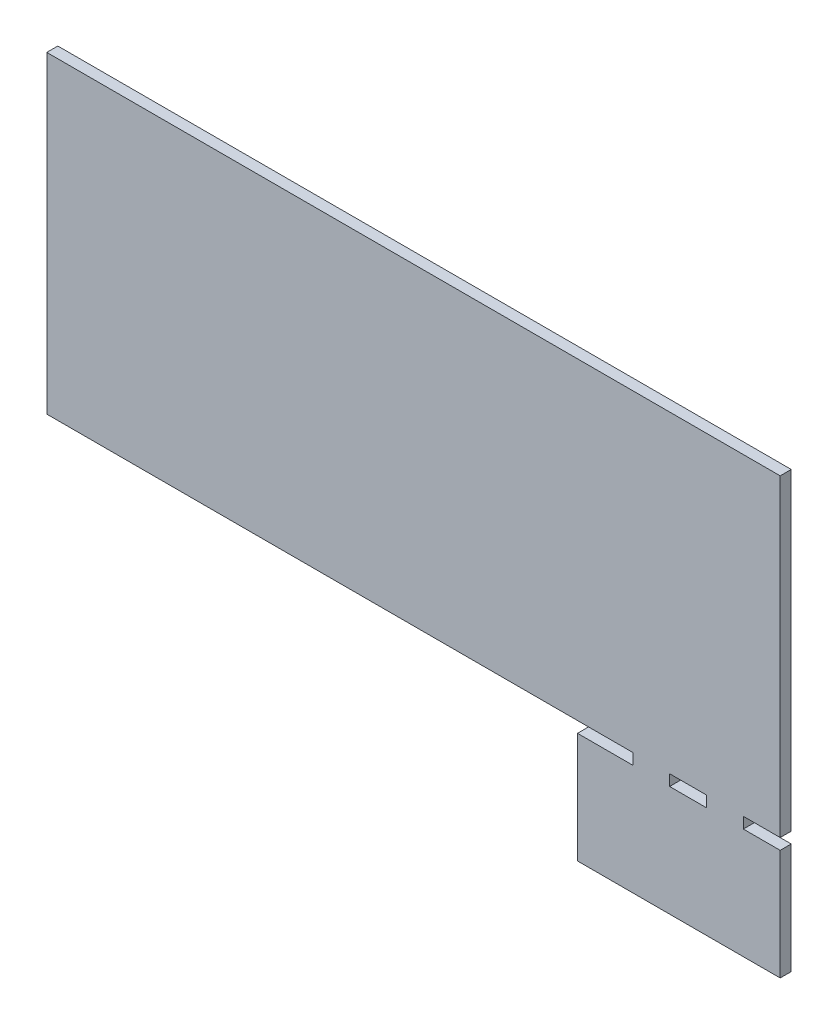
SolidWorks part; units mm, degrees
ref_plane "Front Plane" through (0, 0, 0) normal (0, 0, 1) x (1, 0, 0)
ref_plane "Top Plane" through (0, 0, 0) normal (0, 1, 0) x (1, 0, 0)
ref_plane "Right Plane" through (0, 0, 0) normal (1, 0, 0) x (0, 0, -1)
sketch "Sketch1" plane through (0, 0, 0) normal (0, 0, 1) x (1, 0, 0)
  line L1 (-27.5, -27.5) -> (27.5, -27.5)
  line L2 (-27.5, -27.5) -> (-27.5, 27.5)
  line L3 (-27.5, 27.5) -> (27.5, 27.5)
  line L4 (27.5, -27.5) -> (27.5, 27.5)
  line L5 (0, 27.5) -> (0, -27.5) construction
  line L6 (-27.5, 0) -> (27.5, 0) construction
  point P0 (0, 0)
  dimension "D1" = 55
  dimension "D2" = 55
extrude "Boss-Extrude1" add sketch "Sketch1" along normal blind 3
sketch "Sketch2" plane through (0, 0, 3) normal (0, 0, 1) x (1, 0, 0)
  line L0 (-27.5, -24.5) -> (27.5, -24.5) construction
  line L1 (-27.5, 27.5) -> (-27.5, -27.5) construction
  line L2 (27.5, -27.5) -> (27.5, 27.5) construction
  line L3 (-27.5, -27.5) -> (27.5, -27.5) construction
  line L4 (17.5, -24.5) -> (17.5, -27.5) construction
  line L5 (27.5, -27.5) -> (27.5, 27.5) construction
  line L6 (7.5, -24.5) -> (7.5, -27.5) construction
  line L7 (27.5, -24.5) -> (17.5, -24.5)
  line L8 (27.5, -24.5) -> (27.5, -27.5)
  line L9 (27.5, -27.5) -> (17.5, -27.5)
  line L10 (17.5, -24.5) -> (17.5, -27.5)
  line L11 (-12.5, -24.5) -> (-12.5, -27.5) construction
  line L12 (7.5, -24.5) -> (-2.5, -24.5)
  line L13 (7.5, -24.5) -> (7.5, -27.5)
  line L14 (7.5, -27.5) -> (-2.5, -27.5)
  line L15 (-2.5, -24.5) -> (-2.5, -27.5)
  line L17 (-12.5, -24.5) -> (-27.5, -24.5)
  line L18 (-12.5, -24.5) -> (-12.5, -27.5)
  line L19 (-12.5, -27.5) -> (-27.5, -27.5)
  line L20 (-27.5, -24.5) -> (-27.5, -27.5)
  dimension "D1" = 3
  dimension "D2" = 10
  dimension "D3" = 10
  dimension "D4" = 10
  dimension "D5" = 10
extrude "Cut-Extrude1" cut sketch "Sketch2" against normal blind 3 contours L18 L17 L20 L19 | L13 L12 L15 L14 | L8 L7 L10 L9
sketch "Sketch3" plane through (0, 0, 0) normal (0, 0, -1) x (-1, 0, 0)
  line L0 (-27.5, -24.5) -> (-27.5, -90.5) construction
  line L1 (27.5, -24.5) -> (27.5, -57.5) construction
  line L2 (27.5, -57.5) -> (-27.5, -57.5) construction
  line L3 (-7.5, -27.5) -> (-17.5, -27.5) construction
  line L5 (27.5, -57.5) -> (-27.5, -57.5)
  line L6 (27.5, -57.5) -> (27.5, -27.5)
  line L7 (27.5, -27.5) -> (-27.5, -27.5)
  line L8 (-27.5, -57.5) -> (-27.5, -27.5)
  dimension "D1" = 30
extrude "Boss-Extrude2" add sketch "Sketch3" against normal blind 3
sketch "Sketch4" plane through (0, 0, 0) normal (0, 0, -1) x (-1, 0, 0)
  line L0 (-27.5, 27.5) -> (171.5, 27.5) construction
  line L4 (27.5, -24.5) -> (171.5, -24.5)
  line L5 (27.5, -24.5) -> (27.5, 27.5)
  line L6 (27.5, 27.5) -> (171.5, 27.5)
  line L7 (171.5, -24.5) -> (171.5, 27.5)
  dimension "D1" = 199
extrude "Boss-Extrude3" add sketch "Sketch4" against normal blind 3
sketch "Sketch5" plane through (0, 0, 0) normal (0, 0, -1) x (-1, 0, 0)
  line L0 (-27.5, 27.5) -> (-27.5, 40.5) construction
  line L1 (171.5, 27.5) -> (171.5, 40.5) construction
  line L2 (171.5, 40.5) -> (-27.5, 40.5) construction
  line L3 (12.5, -24.5) -> (171.5, -24.5) construction
  line L4 (-27.5, 27.5) -> (-27.5, 40.5)
  line L5 (-27.5, 40.5) -> (171.5, 40.5)
  line L6 (171.5, 40.5) -> (171.5, 27.5)
  line L7 (171.5, 27.5) -> (-27.5, 27.5)
  dimension "D1" = 65
extrude "Boss-Extrude4" add sketch "Sketch5" against normal blind 3
sketch "Sketch6" plane through (0, 0, 0) normal (0, 0, -1) x (-1, 0, 0)
  line L0 (-27.5, 40.5) -> (-27.5, 60.5) construction
  line L2 (-27.5, 60.5) -> (171.5, 60.5)
  line L3 (-27.5, 60.5) -> (-27.5, 40.5)
  line L4 (-27.5, 40.5) -> (171.5, 40.5)
  line L5 (171.5, 60.5) -> (171.5, 40.5)
  dimension "D1" = 20
extrude "Boss-Extrude5" add sketch "Sketch6" against normal blind 3
sketch "Sketch7" plane through (0, 0, 0) normal (0, 0, -1) x (-1, 0, 0)
  line L0 (41.5, 60.5) -> (41.5, -24.5) construction
  line L1 (171.5, 60.5) -> (-27.5, 60.5) construction
  line L2 (12.5, -24.5) -> (171.5, -24.5) construction
  line L3 (171.5, -24.5) -> (171.5, 60.5) construction
  line L4 (41.5, 25.5) -> (171.5, 25.5) construction
  line L5 (123.5, 41.5) -> (184.4312, 41.5) construction
  line L6 (123.5, 51.5) -> (163.5, 51.5)
  line L7 (123.5, 51.5) -> (123.5, 31.5)
  line L8 (123.5, 31.5) -> (163.5, 31.5)
  line L9 (163.5, 51.5) -> (163.5, 31.5)
  line L10 (168.5, 47.6633) -> (168.5, 37.884) construction
  line L11 (168.5, 37.884) -> (168.5, 28.4787) construction
  line L12 (168.5, 47.6633) -> (168.5, 56.16) construction
  line L13 (163.5, 46.5) -> (168.5, 46.5) construction
  line L14 (143.5, 31.5) -> (143.5, 51.5) construction
  circle A0 centre (168.5, 46.5) radius 2
  circle A1 centre (168.5, 36.5) radius 2
  circle A2 centre (118.5, 36.5) radius 2
  circle A3 centre (118.5, 46.5) radius 2
  dimension "D1" = 130
  dimension "D2" = 50
  dimension "D3" = 20
  dimension "D4" = 40
  dimension "D5" = 6
  dimension "D6" = 8
  dimension "D7" = 5
  dimension "D8" = 5
extrude "Cut-Extrude22" cut sketch "Sketch7" against normal blind 33 contours L7 L6 L9 L8 | A0 | A1 | A2 | A3
sketch "Sketch8" plane through (0, 0, 0) normal (0, 0, -1) x (-1, 0, 0)
  line L0 (123.5, 51.5) -> (123.5, 60.5) construction
  line L1 (171.5, 60.5) -> (-27.5, 60.5) construction
  line L3 (163.5, 51.5) -> (123.5, 51.5)
  line L4 (163.5, 51.5) -> (163.5, 60.5)
  line L5 (163.5, 60.5) -> (123.5, 60.5)
  line L6 (123.5, 51.5) -> (123.5, 60.5)
extrude "Cut-Extrude23" cut sketch "Sketch8" against normal blind 33
sketch "Sketch9" plane through (0, 0, 0) normal (0, 0, -1) x (-1, 0, 0)
  line L1 (171.5, 60.5) -> (107.6839, 60.5)
  line L2 (171.5, 60.5) -> (171.5, 29.5937)
  line L3 (171.5, 29.5937) -> (107.6839, 29.5937)
  line L4 (107.6839, 60.5) -> (107.6839, 29.5937)
extrude "Boss-Extrude6" add sketch "Sketch9" against normal blind 3
